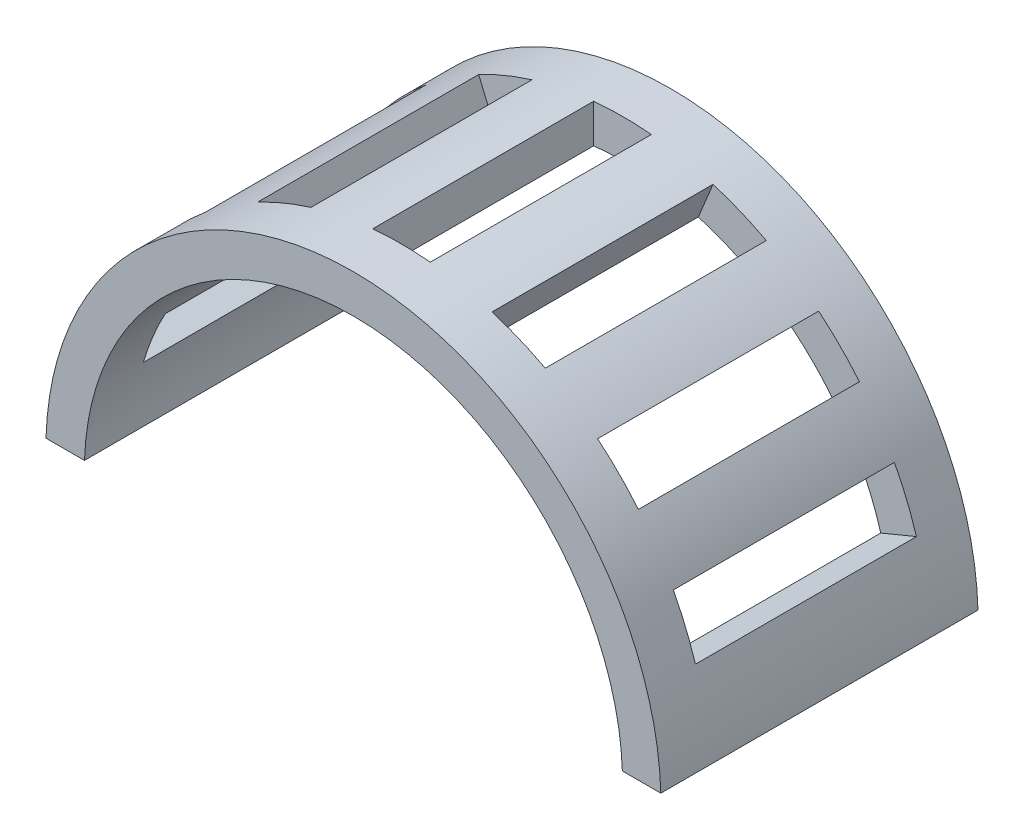
SolidWorks part; units mm, degrees
ref_plane "Plan1" through (0, 0, 0) normal (0, 0, 1) x (1, 0, 0)
ref_plane "Plan2" through (0, 0, 0) normal (0, 1, 0) x (1, 0, 0)
ref_plane "Plan3" through (0, 0, 0) normal (1, 0, 0) x (0, 0, -1)
sketch "Esquisse1" plane through (0, 0, 0) normal (0, 0, 1) x (1, 0, 0)
  line L0 (-15.75, 0) -> (15.9922, 0) construction
  line L1 (13.9911, 0.5) -> (15.9922, 0.5)
  line L2 (-15.9922, 0.5) -> (-13.9911, 0.5)
  line L3 (15.9922, 0.5) -> (15.9922, 0) construction
  arc A0 (15.9922, 0.5) -> (-15.9922, 0.5) centre (0, 0) ccw
  arc A1 (13.9911, 0.5) -> (-13.9911, 0.5) centre (0, 0) ccw
  dimension "D1" = 32
  dimension "D2" = 28
  dimension "D3" = 0.5
extrude "Base-Extrusion" add sketch "Esquisse1" along normal blind 16.5
ref_plane "Plan4" through (0, 0, 8.25) normal (0, 0, 1) x (1, 0, 0)
sketch "Esquisse3" plane through (0, 0, 8.25) normal (0, 0, 1) x (1, 0, 0)
  line L0 (0, 0) -> (0, 19) construction
  line L1 (1.5, 13.9194) -> (1.5, 15.9295)
  line L2 (-1.5, 13.9194) -> (-1.5, 15.9295)
  arc A0 (1.5, 13.9194) -> (-1.5, 13.9194) centre (0, 0) ccw
  arc A1 (1.5, 15.9295) -> (-1.5, 15.9295) centre (0, 0) ccw
  arc A2 (15.9922, 0.5) -> (-15.9922, 0.5) centre (0, 0) ccw construction
  arc A3 (13.9911, 0.5) -> (-13.9911, 0.5) centre (0, 0) ccw construction
  dimension "D1" = 3
extrude "Enlèv. mat.-Extru.1" cut sketch "Esquisse3" against normal mid plane 11.5
pattern_circular "Répétition circulaire1" count 16 every 22.5
sketch "Esquisse4" plane through (0, 0, 16.5) normal (0, 0, 1) x (1, 0, 0)
  line L0 (13.9911, 0.5) -> (15.9922, 0.5)
  line L1 (13.7875, 2.4301) -> (15.7571, 2.7773)
  arc A0 (13.9911, 0.5) -> (13.7875, 2.4301) centre (0, 0) ccw
  arc A1 (15.9922, 0.5) -> (15.7571, 2.7773) centre (0, 0) ccw
  arc A2 (15.9922, 0.5) -> (-15.9922, 0.5) centre (0, 0) ccw construction
  arc A3 (13.9911, 0.5) -> (-13.9911, 0.5) centre (0, 0) ccw construction
  dimension "D1" = 170.004
extrude "Boss.-Extru.1" add sketch "Esquisse4" against normal through all
sketch "Esquisse5" plane through (0, 0, 16.5) normal (0, 0, 1) x (1, 0, 0)
  line L0 (-15.9922, 0.5) -> (-13.9911, 0.5)
  line L1 (-15.6732, 3.2172) -> (-13.7141, 2.8151)
  arc A0 (-15.6732, 3.2172) -> (-15.9922, 0.5) centre (0, 0) ccw
  arc A1 (-13.7141, 2.8151) -> (-13.9911, 0.5) centre (0, 0) ccw
  arc A2 (15.9922, 0.5) -> (-15.9922, 0.5) centre (0, 0) ccw construction
  arc A3 (13.9911, 0.5) -> (-13.9911, 0.5) centre (0, 0) ccw construction
  dimension "D1" = 11.6
extrude "Boss.-Extru.2" add sketch "Esquisse5" against normal through all
